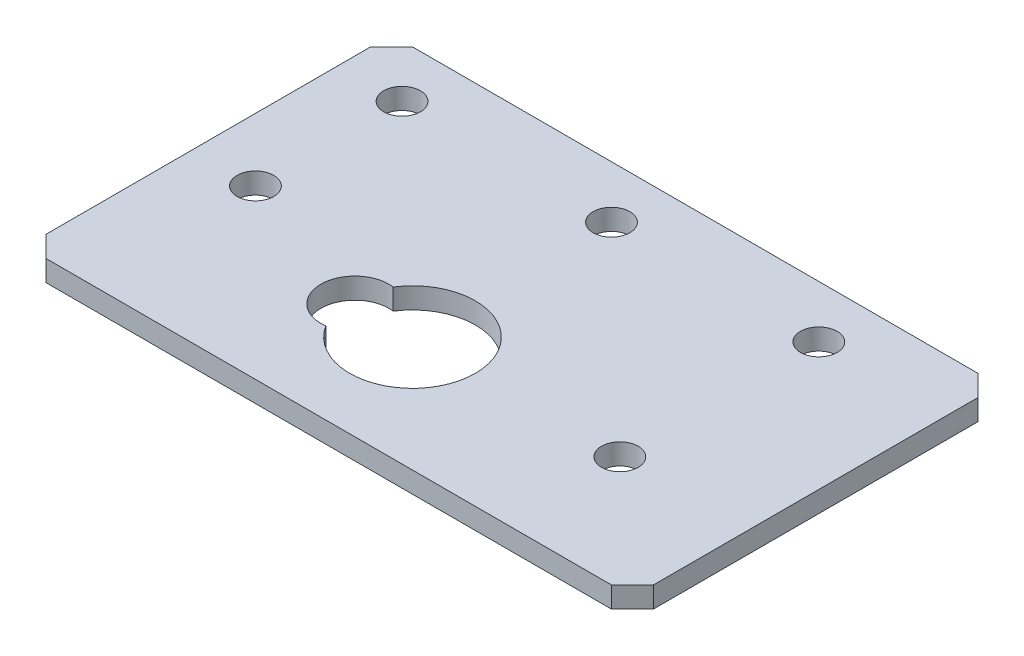
SolidWorks part; units mm, degrees
ref_plane "Front Plane" through (0, 0, 0) normal (0, 0, 1) x (1, 0, 0)
ref_plane "Top Plane" through (0, 0, 0) normal (0, 1, 0) x (1, 0, 0)
ref_plane "Right Plane" through (0, 0, 0) normal (1, 0, 0) x (0, 0, -1)
sketch "Sketch1" plane through (0, 0, 0) normal (0, 1, 0) x (1, 0, 0)
  line L1 (-29, -17.5) -> (29, -17.5)
  line L2 (-29, -17.5) -> (-29, 17.5)
  line L3 (-29, 17.5) -> (29, 17.5)
  line L4 (29, -17.5) -> (29, 17.5)
  line L5 (-29, -17.5) -> (29, 17.5) construction
  line L6 (-29, 17.5) -> (29, -17.5) construction
  point P0 (0, 0)
  dimension "D1" = 35
  dimension "D2" = 58
extrude "Boss-Extrude1" add sketch "Sketch1" along normal blind 2
hole_wizard "M3x0.5 Tapped Hole1" positions "Sketch2" profile "Sketch3" tap size "M3x0.5" standard "JIS" end condition through all
sketch "Sketch2" plane through (0, 2, 0) normal (0, 1, 0) x (1, 0, 0)
  line L0 (-29, -17.5) -> (29, -17.5) construction
  line L1 (29, -17.5) -> (29, 17.5) construction
  point P0 (-23, 12.5)
  point P2 (-3, 12.5)
  point P4 (16.8, 12.5)
  point P6 (16.8, -6.5)
  point P8 (-23, -1.5)
  dimension "D1" = 16
  dimension "D2" = 12.2
  dimension "D3" = 19.8
  dimension "D4" = 20
  dimension "D5" = 19
  dimension "D6" = 11
sketch "Sketch3" plane through (-23, 2, -12.5) normal (1, 0, 0) x (0, 0, 1)
  line L0 (0, 0) -> (0, 2)
  line L1 (0, 2) -> (1.75, 2)
  line L2 (1.75, 2) -> (1.75, -0.225)
  line L3 (1.75, -0.225) -> (1.525, 0)
  line L5 (1.525, 0) -> (0, 0)
  line L6 (-1.75, -0.225) -> (-1.525, 0) construction
  line L11 (0, -6.35) -> (0, 107.95) construction
  dimension "Thru Tap Drill Dia." = 3.5
  dimension "Thru Tap Drill Depth" = 2
  dimension "Near C'Sink Dia." = 3.05
  dimension "Near C'Sink Angle" = 90
cosmetic thread "Hole Thread1" parameters "D2"=4
cosmetic thread "Hole Thread2" parameters "D2"=4
cosmetic thread "Hole Thread3" parameters "D2"=4
cosmetic thread "Hole Thread4" parameters "D2"=4
cosmetic thread "Hole Thread5" parameters "D2"=4
sketch "Sketch4" plane through (0, 2, 0) normal (0, 1, 0) x (1, 0, 0)
  line L0 (-29, 17.5) -> (-29, -17.5) construction
  line L1 (-29, -17.5) -> (29, -17.5) construction
  arc A0 (-8.0625, -3.2796) -> (-8.0625, -9.7204) centre (-8.5, -6.5) ccw
  arc A1 (-8.0625, -9.7204) -> (-8.0625, -3.2796) centre (-3, -6.5) ccw
  dimension "D1" = 6.5
  dimension "D2" = 12
  dimension "D3" = 5.5
  dimension "D4" = 26
  dimension "D5" = 11
extrude "Cut-Extrude1" cut sketch "Sketch4" against normal through all
chamfer "Chamfer1" distance 2 angle 45 4 edges at (-29, 1, -17.5) (-29, 1, 17.5) (29, 1, -17.5) (29, 1, 17.5)
